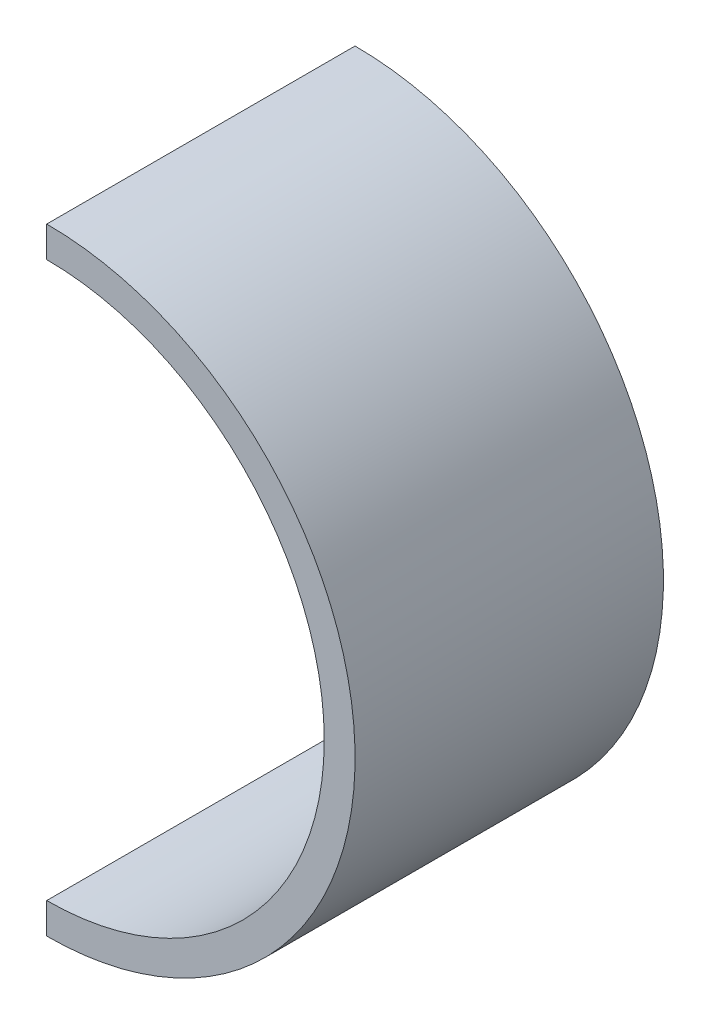
SolidWorks part; units mm, degrees
ref_plane "Front Plane" through (0, 0, 0) normal (0, 0, 1) x (1, 0, 0)
ref_plane "Top Plane" through (0, 0, 0) normal (0, 1, 0) x (1, 0, 0)
ref_plane "Right Plane" through (0, 0, 0) normal (1, 0, 0) x (0, 0, -1)
sketch "Sketch1" plane through (0, 0, 0) normal (0, 0, 1) x (1, 0, 0)
  line L0 (0, 45) -> (0, 50)
  line L1 (0, -45) -> (0, -50)
  arc A0 (0, -50) -> (0, 50) centre (0, 0) ccw
  arc A1 (0, -45) -> (0, 45) centre (0, 0) ccw
  dimension "D1" = 100
  dimension "D2" = 90
extrude "Boss-Extrude1" add sketch "Sketch1" along normal mid plane 50
